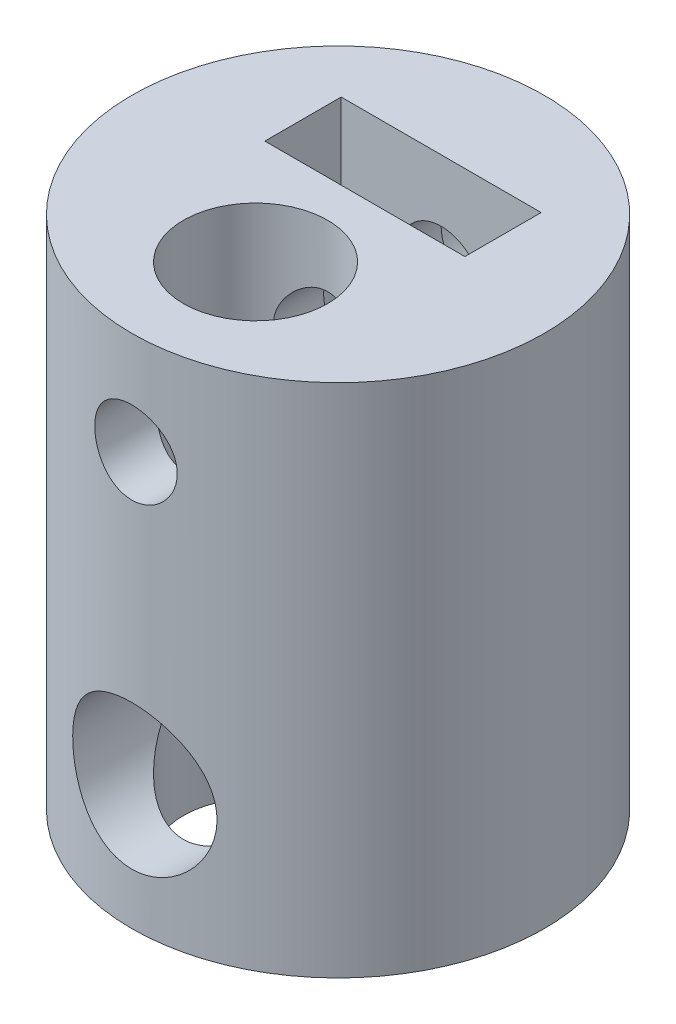
SolidWorks part; units mm, degrees
ref_plane "Alzado" through (0, 0, 0) normal (0, 0, 1) x (1, 0, 0)
ref_plane "Planta" through (0, 0, 0) normal (0, 1, 0) x (1, 0, 0)
ref_plane "Vista lateral" through (0, 0, 0) normal (1, 0, 0) x (0, 0, -1)
sketch "Croquis1" plane through (0, 0, 0) normal (0, 1, 0) x (1, 0, 0)
  circle A0 centre (0, 0) radius 10
  dimension "D1" = 20
extrude "Saliente-Extruir1" add sketch "Croquis1" along normal blind 25
sketch "Croquis3" plane through (0, 25, 0) normal (0, 1, 0) x (1, 0, 0)
  line L0 (0, -4) -> (0, 10) construction
  circle A0 centre (0, -4) radius 3.5
  dimension "D1" = 7
  dimension "D2" = 14
extrude "Cortar-Extruir1" cut sketch "Croquis3" against normal up to next
ref_plane "Plano1" through (10, 0, 0) normal (1, 0, 0) x (0, 0, -1)
ref_plane "Plano2" through (0, 0, -10) normal (0, 0, -1) x (-1, 0, 0)
sketch "Croquis5" plane through (0, 0, -10) normal (0, 0, -1) x (-1, 0, 0)
  line L0 (0, 0) -> (0, 6) construction
  line L1 (-10, 25) -> (10, 25) construction
  line L2 (-10, 25) -> (-10, 0) construction
  line L3 (-10, 0) -> (10, 0) construction
  line L4 (10, 25) -> (10, 0) construction
  line L5 (10, 12.5) -> (7.7498, 12.5) construction
  line L6 (0, 20) -> (0, 25) construction
  circle A0 centre (0, 6) radius 3.5
  circle A1 centre (0, 20) radius 2
  dimension "D2" = 7
  dimension "D3" = 4
  dimension "D1" = 6
  dimension "D4" = 5
extrude "Cortar-Extruir3" cut sketch "Croquis5" against normal through all
sketch "Croquis6" plane through (0, 0, 0) normal (0, -1, 0) x (1, 0, 0)
  line L0 (0, -10) -> (0, -5) construction
  line L1 (0, -5) -> (0, -1.3) construction
  line L2 (-4.85, -5) -> (-4.85, -1.3)
  line L3 (4.85, -5) -> (-4.85, -5)
  line L4 (4.85, -5) -> (4.85, -1.3)
  line L5 (4.85, -1.3) -> (-4.85, -1.3)
  circle A0 centre (0, 0) radius 10 construction
  dimension "D1" = 5
  dimension "D3" = 3.7
  dimension "D4" = 4.85
extrude "Cortar-Extruir4" cut sketch "Croquis6" against normal up to next
sketch "Croquis7" plane through (0, 0, -10) normal (0, 0, -1) x (-1, 0, 0)
  circle A0 centre (0, 20) radius 3.5
  dimension "D1" = 7
extrude "Cortar-Extruir5" cut sketch "Croquis7" against normal blind 3
